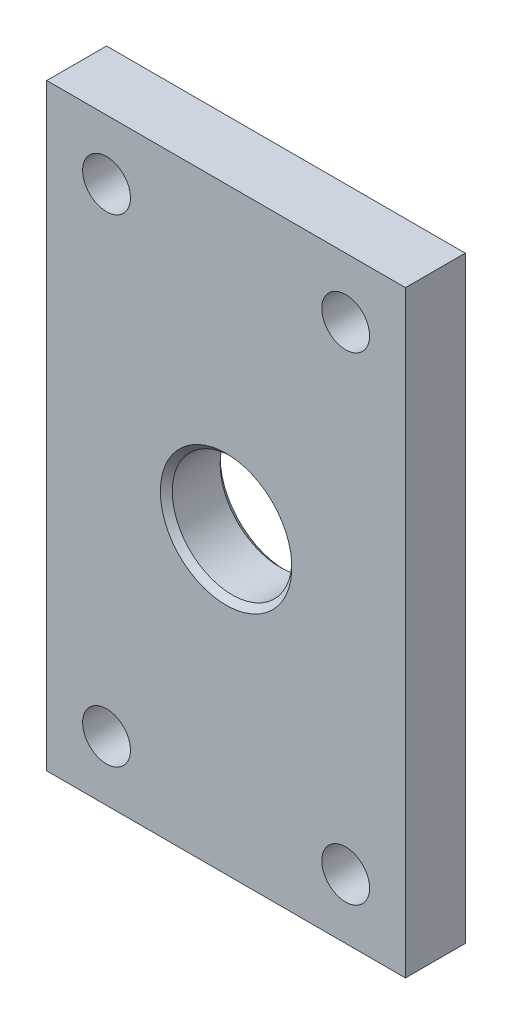
SolidWorks part; units mm, degrees
ref_plane "Front Plane" through (0, 0, 0) normal (1, 0, 0) x (0, 1, 0)
ref_plane "Top Plane" through (0, 0, 0) normal (0, 0, 1) x (0, 1, 0)
ref_plane "Right Plane" through (0, 0, 0) normal (0, 1, 0) x (-1, 0, 0)
sketch "Sketch1" plane through (0, 0, 0) normal (0, 0, 1) x (0, 1, 0)
  line L1 (-50, -30) -> (50, -30)
  line L2 (-50, -30) -> (-50, 30)
  line L3 (-50, 30) -> (50, 30)
  line L4 (50, -30) -> (50, 30)
  line L5 (-50, -30) -> (50, 30) construction
  line L6 (-50, 30) -> (50, -30) construction
  point P0 (0, 0)
extrude "Boss-Extrude1" add sketch "Sketch1" along normal mid plane 10
sketch "Sketch2" plane through (0, 0, 0) normal (0, 0, 1) x (0, 1, 0)
  circle A0 centre (-40, -20) radius 4
extrude "Cut-Extrude2" cut sketch "Sketch2" against normal through all from offset 5
sketch "Sketch3" plane through (0, 0, 0) normal (0, 0, 1) x (0, 1, 0)
  circle A0 centre (40, -20) radius 4
  circle A1 centre (-40, 20) radius 4
  circle A2 centre (40, 20) radius 4
extrude "Cut-Extrude4" cut sketch "Sketch3" against normal through all from offset 5
sketch "Sketch4" plane through (0, 0, 0) normal (0, 0, 1) x (0, 1, 0)
  circle A0 centre (0, 0) radius 10
extrude "Cut-Extrude6" cut sketch "Sketch4" against normal through all from offset 5
chamfer "Chamfer1" distance 1 angle 45 2 edges at (10, 0, -5) (10, 0, 5)
